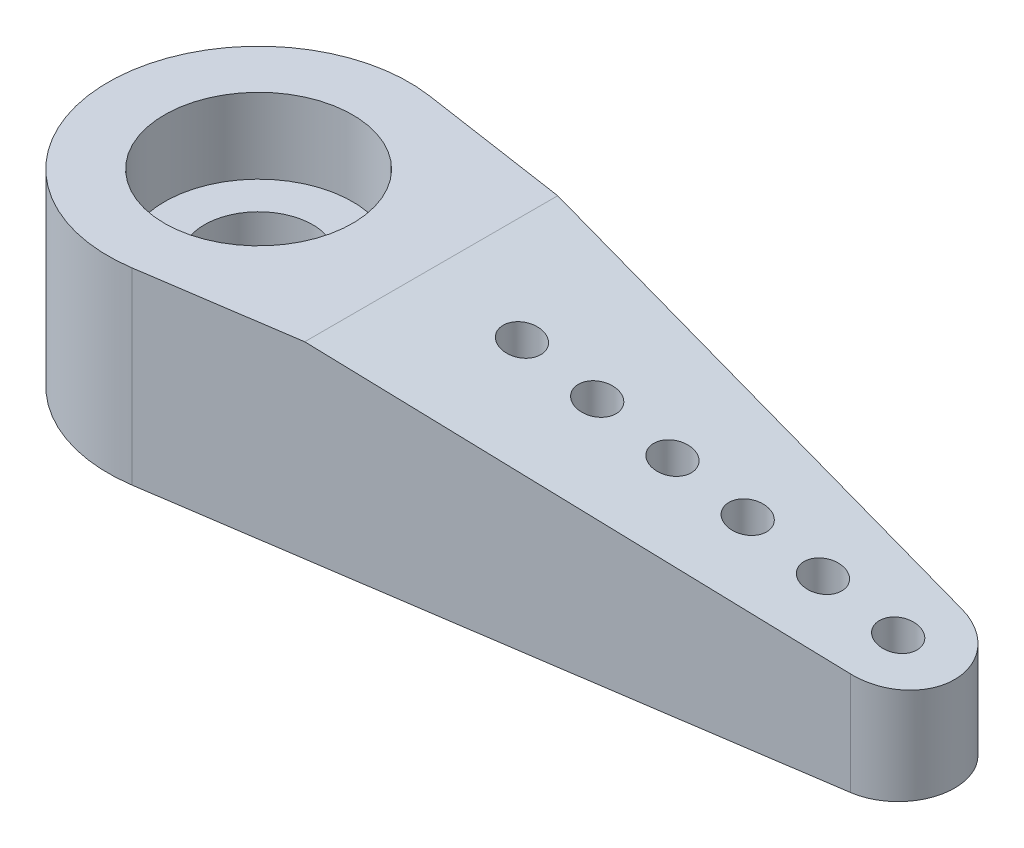
SolidWorks part; units mm, degrees
ref_plane "Спереди" through (0, 0, 0) normal (0, 0, 1) x (1, 0, 0)
ref_plane "Сверху" through (0, 0, 0) normal (0, 1, 0) x (1, 0, 0)
ref_plane "Справа" through (0, 0, 0) normal (1, 0, 0) x (0, 0, -1)
sketch "Эскиз1" plane through (0, 0, 0) normal (0, 1, 0) x (1, 0, 0)
  line L3 (1.1765, 7.913) -> (34.4412, 2.9674)
  line L4 (1.1765, -7.913) -> (34.4412, -2.9674)
  arc A0 (1.1765, 7.913) -> (1.1765, -7.913) centre (0, 0) ccw
  arc A1 (34.4412, -2.9674) -> (34.4412, 2.9674) centre (34, 0) ccw
  dimension "D1" = 6
  dimension "D3" = 16
  dimension "D2" = 34
extrude "Бобышка-Вытянуть1" add sketch "Эскиз1" along normal blind 10
sketch "Эскиз3" plane through (0, 0, 0) normal (0, 0, 1) x (1, 0, 0)
  line L1 (1.1765, 10) -> (34.4412, 10) construction
  line L3 (37, 0) -> (37, 10) construction
  line L4 (37, 5) -> (9.1765, 10)
  line L5 (9.1765, 10) -> (37, 10)
  line L6 (37, 10) -> (37, 5)
extrude "Вырез-Вытянуть1" cut sketch "Эскиз3" against normal through all both and the other way through all
sketch "Эскиз4" plane through (0, 10, 0) normal (0, 1, 0) x (1, 0, 0)
  circle A1 centre (0, 0) radius 5
extrude "Вырез-Вытянуть2" cut sketch "Эскиз4" against normal blind 4
sketch "Эскиз5" plane through (0, 6, 0) normal (0, 1, 0) x (1, 0, 0)
  circle A0 centre (0, 0) radius 2.88
extrude "Вырез-Вытянуть3" cut sketch "Эскиз5" against normal blind 6
sketch "Эскиз6" plane through (0, 0, 0) normal (0, -1, 0) x (1, 0, 0)
  circle A2 centre (34, 0) radius 1
  circle A7 centre (30, 0) radius 1
  circle A8 centre (26, 0) radius 1
  circle A9 centre (22, 0) radius 1
  circle A10 centre (18, 0) radius 1
  circle A11 centre (14, 0) radius 1
  dimension "D1" = 6
extrude "Вырез-Вытянуть4" cut sketch "Эскиз6" against normal through all
